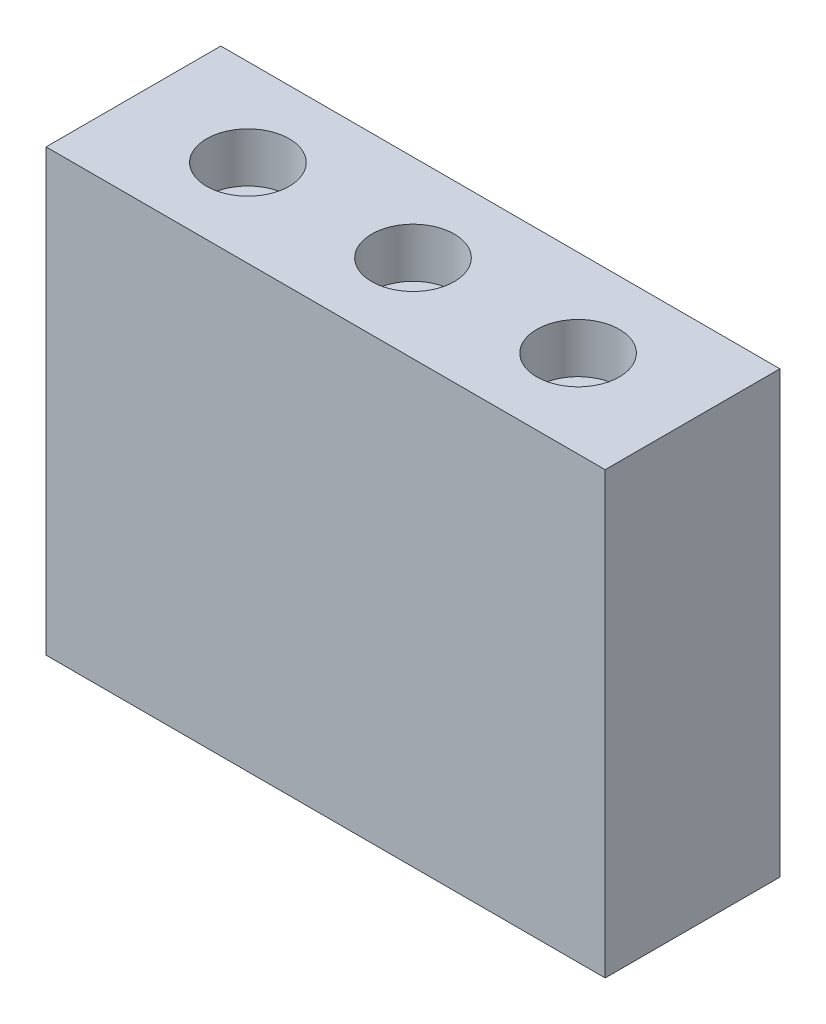
SolidWorks part; units mm, degrees
material "Low Carbon Steel"
ref_plane "Front Plane" through (0, 0, 0) normal (0, 0, 1) x (1, 0, 0)
ref_plane "Top Plane" through (0, 0, 0) normal (0, 1, 0) x (1, 0, 0)
ref_plane "Right Plane" through (0, 0, 0) normal (1, 0, 0) x (0, 0, -1)
sketch "Sketch1" plane through (0, 0, 0) normal (0, 0, 1) x (1, 0, 0)
  line L0 (-50.8, -2.55) -> (50.8, -2.55)
  line L1 (-50.8, 80) -> (50.8, 80)
  line L2 (-50.8, 80) -> (-50.8, -2.55)
  line L3 (-50.8, 0) -> (50.8, 0) construction
  line L4 (50.8, 80) -> (50.8, -2.55)
  dimension "D1" = 101.6
  dimension "D2" = 82.55
  dimension "D3" = 80
extrude "Boss-Extrude1" add sketch "Sketch1" along normal mid plane 31.75
sketch "Sketch2" plane through (0, 0, 15.875) normal (0, 0, 1) x (1, 0, 0)
  line L0 (50.8, -2.55) -> (50.8, 80) construction
  line L1 (-50.8, -2.55) -> (50.8, -2.55)
  line L2 (-50.8, -2.55) -> (-50.8, 0)
  line L3 (-50.8, 0) -> (50.8, 0)
  line L4 (50.8, -2.55) -> (50.8, 0)
extrude "Cut-Extrude1" cut sketch "Sketch2" against normal through all
hole_wizard "CBORE for M8 Hex Socket Head Cap Screw1" positions "Sketch4" profile "Sketch3" counterbore size "M8" standard "Peddi DIN"
sketch "Sketch4" plane through (0, 80, 0) normal (0, 1, 0) x (1, 0, 0)
  line L0 (-30, 0) -> (30, 0) construction
  point P0 (30, 0)
  point P2 (0, 0)
  point P4 (-30, 0)
  dimension "D1" = 60
sketch "Sketch3" plane through (30, 80, 0) normal (1, 0, 0) x (0, 0, 1)
  line L0 (0, 0) -> (0, 80)
  line L1 (0, 80) -> (4.5, 80)
  line L3 (4.5, 80) -> (4.5, 9)
  line L4 (4.5, 9) -> (7.5, 9)
  line L5 (7.5, 9) -> (7.5, 0)
  line L7 (7.5, 0) -> (0, 0)
  line L11 (0, -6.35) -> (0, 107.95) construction
  dimension "Thru Hole Dia." = 9
  dimension "Thru Hole Depth" = 80
  dimension "C'Bore Dia." = 15
  dimension "C'Bore Depth" = 9
other "Freeze***"
